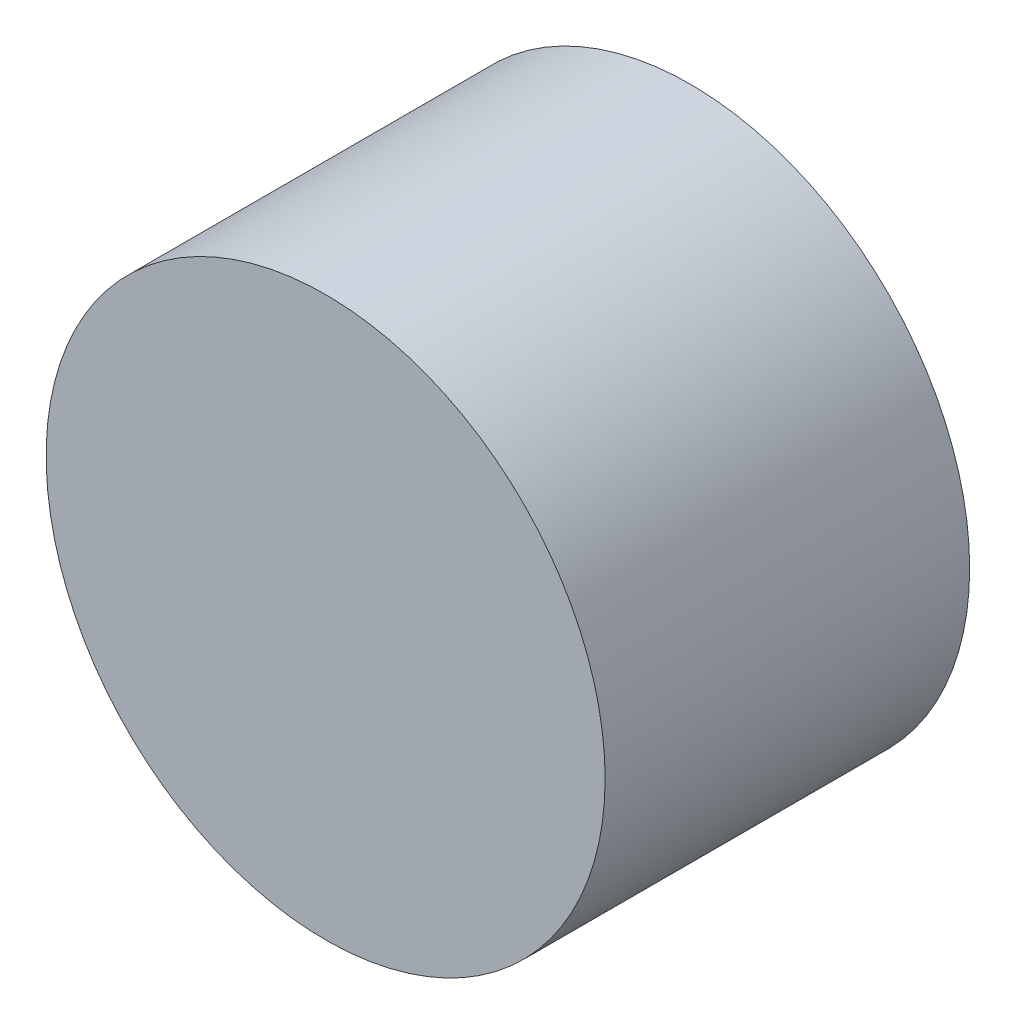
SolidWorks part; units mm, degrees
ref_plane "Front Plane" through (0, 0, 0) normal (0, 0, 1) x (1, 0, 0)
ref_plane "Top Plane" through (0, 0, 0) normal (0, 1, 0) x (1, 0, 0)
ref_plane "Right Plane" through (0, 0, 0) normal (1, 0, 0) x (0, 0, -1)
sketch "Sketch1" plane through (0, 0, 0) normal (0, 0, 1) x (1, 0, 0)
  circle A0 centre (0, 0) radius 11.5
  dimension "D1" = 23
extrude "Boss-Extrude1" add sketch "Sketch1" along normal blind 15
